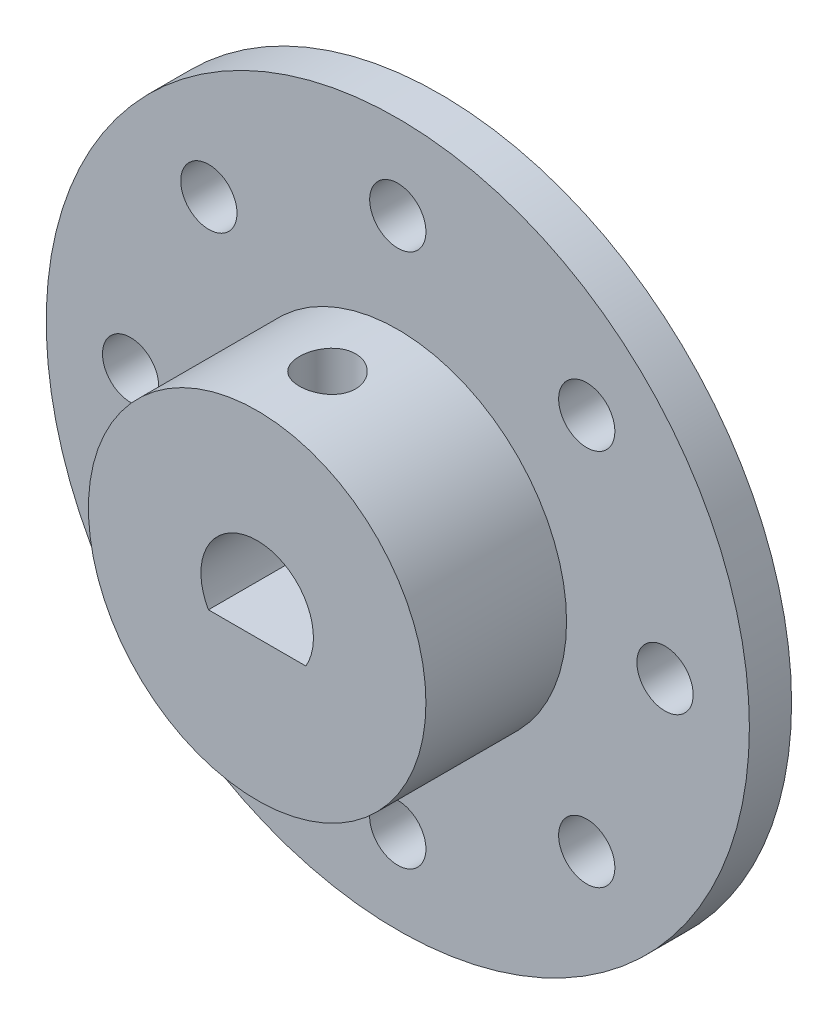
SolidWorks part; units mm, degrees
material "合金钢"
ref_plane "前视基准面" through (0, 0, 0) normal (0, 0, 1) x (1, 0, 0)
ref_plane "上视基准面" through (0, 0, 0) normal (0, 1, 0) x (1, 0, 0)
ref_plane "右视基准面" through (0, 0, 0) normal (1, 0, 0) x (0, 0, -1)
sketch "草图1" plane through (0, 0, 0) normal (0, 0, 1) x (1, 0, 0)
  line L0 (0, 0) -> (0, 19) construction
  circle A0 centre (0, 0) radius 25
  circle A1 centre (0, 0) radius 19 construction
  circle A2 centre (0, 19) radius 2
  circle A3 centre (13.435, 13.435) radius 2
  circle A4 centre (19, 0) radius 2
  circle A5 centre (13.435, -13.435) radius 2
  circle A6 centre (0, -19) radius 2
  circle A7 centre (-13.435, -13.435) radius 2
  circle A8 centre (-19, 0) radius 2
  circle A9 centre (-13.435, 13.435) radius 2
  circle A10 centre (0, 0) radius 4
  point P23 (0, 0)
  dimension "D1" = 8
extrude "凸台-拉伸1" add sketch "草图1" along normal blind 3
sketch "草图2" plane through (0, 0, 3) normal (0, 0, 1) x (1, 0, 0)
  circle A0 centre (0, 0) radius 12
extrude "凸台-拉伸2" add sketch "草图2" along normal blind 10
sketch "草图3" plane through (0, 0, 13) normal (0, 0, 1) x (1, 0, 0)
  line L0 (-4, 0) -> (4, 0) construction
  line L1 (-3.4641, -2) -> (3.4641, -2)
  line L2 (-4, -2) -> (4, -2) construction
  arc A0 (3.4641, -2) -> (-3.4641, -2) centre (0, 0) ccw
  dimension "D1" = 2
extrude "切除-拉伸1" cut sketch "草图3" against normal blind 24 contours A0 L1
sketch "草图4" plane through (0, -2, 0) normal (0, 1, 0) x (1, 0, 0)
  line L0 (0, -13) -> (0, -3) construction
  line L1 (-12, -13) -> (12, -13) construction
  line L2 (-12, -3) -> (12, -3) construction
  circle A0 centre (0, -8) radius 2
extrude "切除-拉伸2" cut sketch "草图4" along normal blind 19
